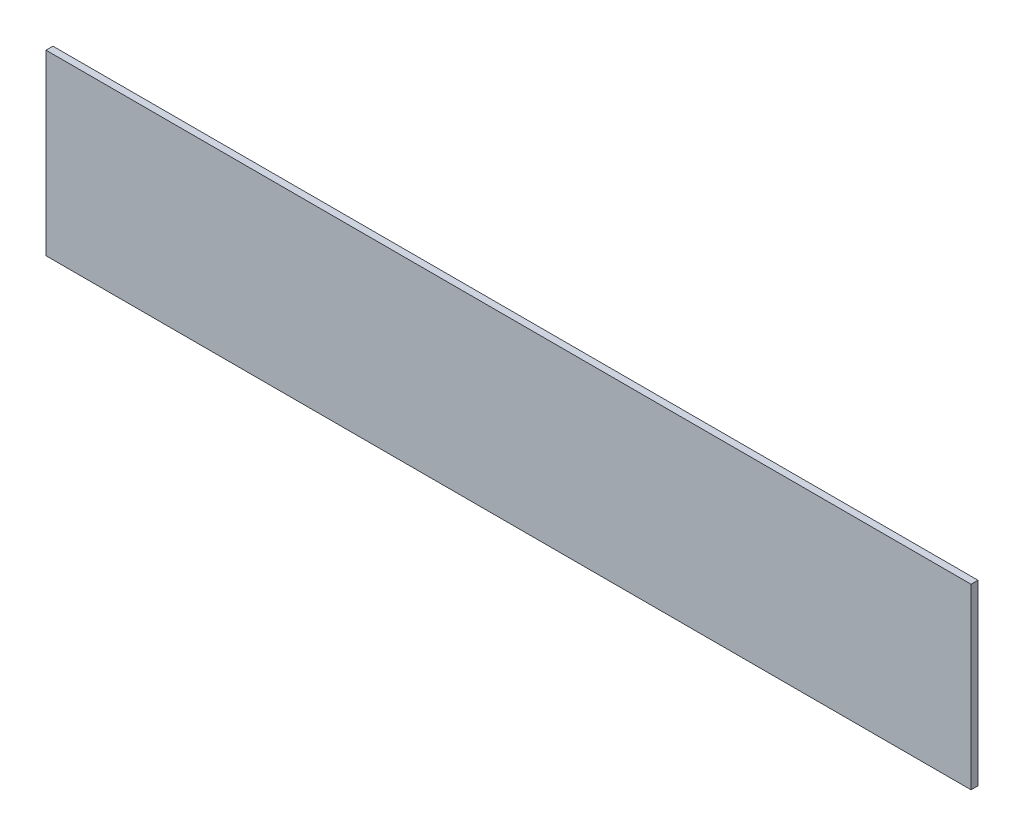
SolidWorks part; units mm, degrees
ref_plane "Płaszczyzna przednia" through (0, 0, 0) normal (0, 0, 1) x (1, 0, 0)
ref_plane "Płaszczyzna górna" through (0, 0, 0) normal (0, 1, 0) x (1, 0, 0)
ref_plane "Płaszczyzna prawa" through (0, 0, 0) normal (1, 0, 0) x (0, 0, -1)
sketch "Szkic1" plane through (0, 0, 0) normal (0, 0, 1) x (1, 0, 0)
  line L1 (-167.4879, -68.9656) -> (232.5121, -68.9656)
  line L2 (-167.4879, -68.9656) -> (-167.4879, -145.9656)
  line L3 (-167.4879, -145.9656) -> (232.5121, -145.9656)
  line L4 (232.5121, -68.9656) -> (232.5121, -145.9656)
  dimension "D1" = 400
  dimension "D2" = 77
extrude "Dodanie-wyciągnięcie1" add sketch "Szkic1" along normal blind 3
